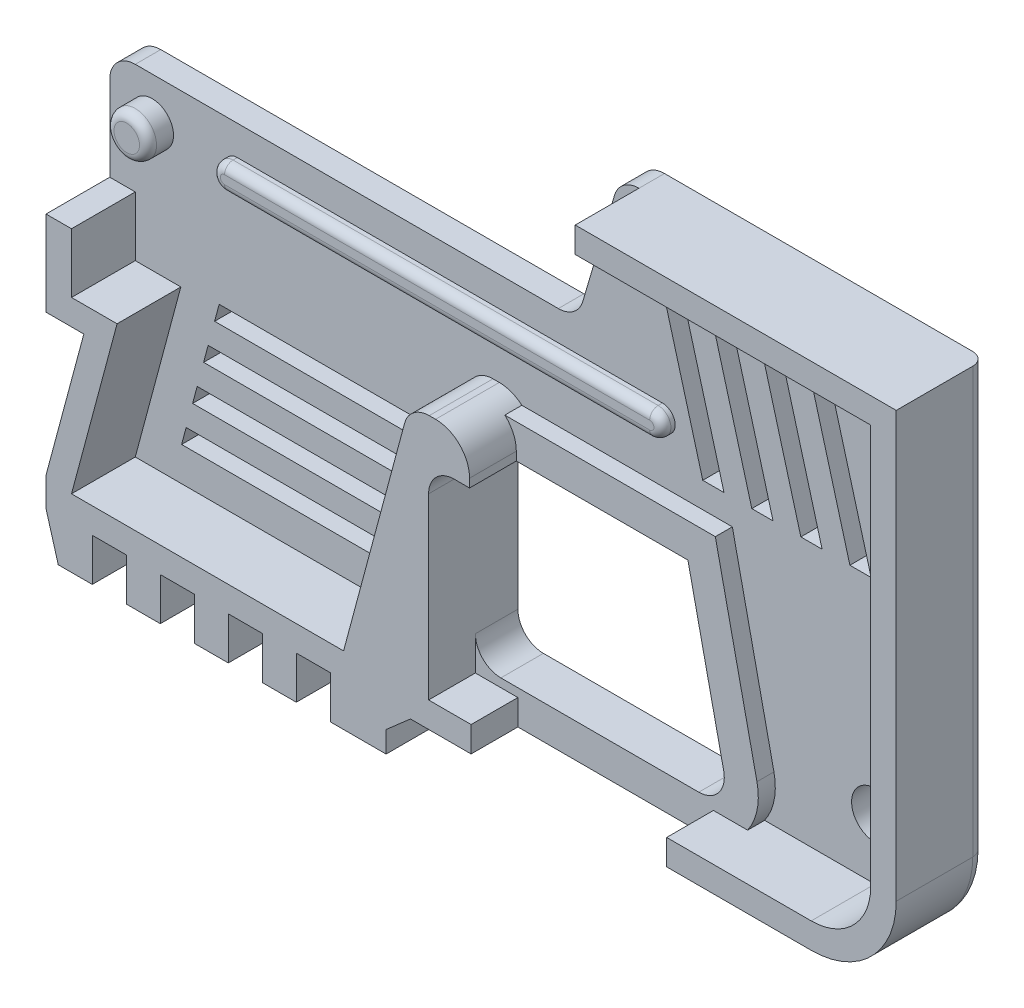
SolidWorks part; units mm, degrees
ref_plane "Front Plane" through (0, 0, 0) normal (0, 0, 1) x (1, 0, 0)
ref_plane "Top Plane" through (0, 0, 0) normal (0, 1, 0) x (1, 0, 0)
ref_plane "Right Plane" through (0, 0, 0) normal (1, 0, 0) x (0, 0, -1)
sketch "Sketch1" plane through (0, 0, 0) normal (0, 0, 1) x (1, 0, 0)
  line L0 (0.6334, 2.1535) -> (4.3666, 14.8465)
  line L1 (7.2447, 17) -> (45, 17)
  line L2 (45, 17) -> (45, -33)
  line L3 (35, -43) -> (-55, -43)
  line L4 (-55, -43) -> (-55, -3)
  line L5 (-52, 0) -> (-2.2447, 0)
  arc A0 (-55, -3) -> (-52, 0) centre (-52, -3) cw
  arc A1 (4.3666, 14.8465) -> (7.2447, 17) centre (7.2447, 14) cw
  arc A2 (0.6334, 2.1535) -> (-2.2447, 0) centre (-2.2447, 3) cw
  arc A3 (45, -33) -> (35, -43) centre (35, -33) cw
  point P9 (-55, 0)
  point P12 (5, 17)
  point P15 (0, 0)
  point P18 (45, -43)
  dimension "D6" = 3
  dimension "D7" = 3
  dimension "D8" = 10
  dimension "D1" = 100
  dimension "D2" = 60
  dimension "D3" = 17
  dimension "D4" = 40
  dimension "D5" = 55
extrude "Boss-Extrude1" add sketch "Sketch1" along normal blind 3
sketch "Sketch2" plane through (0, 0, 3) normal (0, 0, 1) x (1, 0, 0)
  line L0 (-7, -16) -> (15, -16)
  line L1 (15, -16) -> (19.2093, -35.3627)
  line L2 (16.2778, -39) -> (-7, -39)
  line L3 (-10, -36) -> (-10, -19)
  line L4 (-55, -43) -> (35, -43) construction
  line L5 (45, -33) -> (45, 17) construction
  arc A0 (19.2093, -35.3627) -> (16.2778, -39) centre (16.2778, -36) cw
  arc A1 (-7, -39) -> (-10, -36) centre (-7, -36) cw
  arc A2 (-7, -16) -> (-10, -19) centre (-7, -19) ccw
  point P11 (20, -39)
  point P14 (-10, -39)
  point P17 (-10, -16)
  dimension "D6" = 3
  dimension "D1" = 4
  dimension "D2" = 23
  dimension "D3" = 30
  dimension "D4" = 25
  dimension "D5" = 25
extrude "Cut-Extrude1" cut sketch "Sketch2" against normal through all
sketch "Sketch3" plane through (0, 0, 3) normal (0, 0, 1) x (1, 0, 0)
  line L0 (45, -33) -> (45, 17) construction
  line L1 (45, 17) -> (7.2447, 17) construction
  line L2 (45, -33) -> (45, 17)
  line L3 (45, 17) -> (7.2447, 17)
  line L4 (35, -43) -> (18, -43)
  line L5 (-55, -43) -> (35, -43) construction
  line L6 (35, -40) -> (18, -40)
  line L7 (42, -33) -> (42, 14)
  line L8 (42, 14) -> (7.2447, 14)
  line L9 (7.2447, 14) -> (7.2447, 17)
  line L10 (18, -40) -> (18, -43)
  line L11 (-5, -43) -> (-55, -43)
  line L12 (-55, -43) -> (-55, -13)
  line L13 (-55, -3) -> (-55, -43) construction
  line L14 (-55, -13) -> (-52, -13)
  line L15 (-52, -13) -> (-52, -40)
  line L16 (-52, -40) -> (-5, -40)
  line L17 (-5, -40) -> (-5, -43)
  arc A0 (35, -43) -> (45, -33) centre (35, -33) ccw construction
  arc A1 (35, -43) -> (45, -33) centre (35, -33) ccw
  arc A2 (35, -40) -> (42, -33) centre (35, -33) ccw
  dimension "D2" = 17
  dimension "D3" = 3
  dimension "D4" = 30
  dimension "D5" = 50
  dimension "D1" = 3
extrude "Boss-Extrude2" add sketch "Sketch3" along normal blind 7.5
sketch "Sketch4" plane through (0, 0, 3) normal (0, 0, 1) x (1, 0, 0)
  line L0 (15, -16) -> (-7, -16) construction
  line L1 (-10, -19) -> (-10, -36) construction
  line L2 (-7, -39) -> (16.2778, -39) construction
  line L3 (19.2093, -35.3627) -> (15, -16) construction
  line L4 (15, -16) -> (-7, -16)
  line L5 (-10, -19) -> (-10, -36)
  line L6 (-7, -39) -> (16.2778, -39)
  line L7 (19.2093, -35.3627) -> (15, -16)
  line L8 (18.2239, -12) -> (-7, -12)
  line L9 (-14, -19) -> (-14, -36)
  line L10 (-7, -43) -> (16.2778, -43)
  line L11 (23.118, -34.513) -> (18.2239, -12)
  arc A0 (-7, -16) -> (-10, -19) centre (-7, -19) ccw construction
  arc A1 (-10, -36) -> (-7, -39) centre (-7, -36) ccw construction
  arc A2 (16.2778, -39) -> (19.2093, -35.3627) centre (16.2778, -36) ccw construction
  arc A3 (-7, -16) -> (-10, -19) centre (-7, -19) ccw
  arc A4 (-10, -36) -> (-7, -39) centre (-7, -36) ccw
  arc A5 (16.2778, -39) -> (19.2093, -35.3627) centre (16.2778, -36) ccw
  arc A6 (-7, -12) -> (-14, -19) centre (-7, -19) ccw
  arc A7 (-14, -36) -> (-7, -43) centre (-7, -36) ccw
  arc A8 (16.2778, -43) -> (23.118, -34.513) centre (16.2778, -36) ccw
  dimension "D1" = 4
extrude "Boss-Extrude3" add sketch "Sketch4" along normal blind 2
sketch "Sketch5" plane through (0, 0, 3) normal (0, 0, 1) x (1, 0, 0)
  line L0 (9.2447, 11) -> (14.7447, -9)
  line L1 (14.7447, -9) -> (17.2447, -9)
  line L2 (17.2447, -9) -> (11.7447, 11)
  line L3 (11.7447, 11) -> (9.2447, 11)
  line L4 (7.2447, 14) -> (42, 14) construction
  line L5 (23.0125, -9) -> (17.5125, 11)
  line L6 (17.5125, 11) -> (15.0125, 11)
  line L7 (15.0125, 11) -> (20.5125, -9)
  line L8 (20.5125, -9) -> (23.0125, -9)
  line L9 (28.7802, -9) -> (23.2802, 11)
  line L10 (23.2802, 11) -> (20.7802, 11)
  line L11 (20.7802, 11) -> (26.2802, -9)
  line L12 (26.2802, -9) -> (28.7802, -9)
  line L13 (34.548, -9) -> (29.048, 11)
  line L14 (29.048, 11) -> (26.548, 11)
  line L15 (26.548, 11) -> (32.048, -9)
  line L16 (32.048, -9) -> (34.548, -9)
  dimension "D1" = 20
  dimension "D2" = 8
  dimension "D3" = 2.5
  dimension "D4" = 3
  dimension "D5" = 2
  dimension "D6" = 4
extrude "Cut-Extrude2" cut sketch "Sketch5" against normal through all
sketch "Sketch6" plane through (0, 0, 3) normal (0, 0, 1) x (1, 0, 0)
  line L0 (-52, -40) -> (-46.641, -20)
  line L1 (-46.641, -20) -> (-52, -20)
  line L2 (-52, -40) -> (-52, -13) construction
  line L3 (-52, -20) -> (-52, -40)
  dimension "D1" = 15
  dimension "D2" = 20
extrude "Boss-Extrude4" add sketch "Sketch6" along normal blind 7.5
sketch "Sketch7" plane through (0, 0, 10.5) normal (0, 0, 1) x (1, 0, 0)
  line L2 (-55, -13) -> (-55, -43) construction
  line L3 (-55, -39.605) -> (-55, -23)
  line L4 (-54.8978, -39.2235) -> (-50.5507, -23)
  line L5 (-50.5507, -23) -> (-52, -23)
  line L6 (-55, -39.605) -> (-50.5507, -23)
  line L7 (-50.5507, -23) -> (-55, -23)
  dimension "D1" = 3
extrude "Cut-Extrude3" cut sketch "Sketch7" against normal through all
sketch "Sketch8" plane through (0, 0, 3) normal (0, 0, 1) x (1, 0, 0)
  line L0 (-10, -40) -> (-10, -19)
  line L1 (-5, -40) -> (-52, -40) construction
  line L2 (-7, -16) -> (-5.1831, -16)
  line L3 (-5.1831, -16) -> (-5.1831, -11)
  line L4 (-5.1831, -11) -> (-9.9275, -11)
  line L5 (-12.8253, -13.2235) -> (-20, -40)
  line L6 (-52, -40) -> (-46.641, -20) construction
  line L7 (15, -16) -> (-7, -16) construction
  line L8 (-20, -40) -> (-10, -40)
  arc A0 (-10, -19) -> (-7, -16) centre (-7, -19) cw
  arc A1 (-9.9275, -11) -> (-12.8253, -13.2235) centre (-9.9275, -14) ccw
  dimension "D1" = 3
  dimension "D2" = 3
  dimension "D3" = 5
  dimension "D4" = 10
extrude "Boss-Extrude5" add sketch "Sketch8" along normal blind 7.5
sketch "Sketch9" plane through (0, 0, 3) normal (0, 0, 1) x (1, 0, 0)
  line L0 (-40, -5) -> (10, -5) construction
  line L1 (-40, -3.5) -> (10, -3.5)
  line L2 (-40, -6.5) -> (10, -6.5)
  line L3 (-2.2447, 0) -> (-52, 0) construction
  line L4 (-55, -3) -> (-55, -13) construction
  arc A0 (-40, -3.5) -> (-40, -6.5) centre (-40, -5) ccw
  arc A1 (10, -6.5) -> (10, -3.5) centre (10, -5) ccw
  point P2 (-15, -5)
  point P9 (-27.1224, 0)
  dimension "D1" = 3
  dimension "D2" = 50
  dimension "D3" = 5
  dimension "D4" = 15
sketch "Sketch10" plane through (0, 0, 3) normal (0, 0, 1) x (1, 0, 0)
  line L0 (-2.2447, 0) -> (-52, 0) construction
  line L1 (-55, -3) -> (-55, -13) construction
  circle A0 centre (-50, -5) radius 2.5
  dimension "D3" = 5
  dimension "D1" = 5
  dimension "D2" = 5
extrude "Boss-Extrude6" add sketch "Sketch10" along normal blind 3
fillet "Fillet2" radius 1 1 edges at (-47.5, -5, 6)
sketch "Sketch11" plane through (0, 0, 3) normal (0, 0, 1) x (1, 0, 0)
  circle A0 centre (35, -33) radius 2.75
  dimension "D1" = 5.5
extrude "Cut-Extrude5" cut sketch "Sketch11" against normal through all
fillet "Fillet3" radius 1.5 3 edges at (-10, -43, 0) (42.0711, -40.0711, 0) (45, -8, 0)
sketch "Sketch12" plane through (0, 0, 3) normal (0, 0, 1) x (1, 0, 0)
  line L0 (-46.5517, -36) -> (-22.5517, -36)
  line L1 (-22.5517, -36) -> (-22.0158, -34)
  line L2 (-22.0158, -34) -> (-46.0158, -34)
  line L3 (-46.0158, -34) -> (-46.5517, -36)
  line L4 (-52, -40) -> (-46.641, -20) construction
  line L5 (-12.8253, -13.2235) -> (-20, -40) construction
  line L6 (-20, -40) -> (-52, -40) construction
  line L7 (-45.2576, -31.1704) -> (-21.2576, -31.1704)
  line L8 (-21.2576, -31.1704) -> (-20.7217, -29.1704)
  line L9 (-20.7217, -29.1704) -> (-44.7217, -29.1704)
  line L10 (-44.7217, -29.1704) -> (-45.2576, -31.1704)
  line L11 (-43.9635, -26.3407) -> (-19.9635, -26.3407)
  line L12 (-19.9635, -26.3407) -> (-19.4276, -24.3407)
  line L13 (-19.4276, -24.3407) -> (-43.4276, -24.3407)
  line L14 (-43.4276, -24.3407) -> (-43.9635, -26.3407)
  line L15 (-42.6694, -21.5111) -> (-18.6694, -21.5111)
  line L16 (-18.6694, -21.5111) -> (-18.1335, -19.5111)
  line L17 (-18.1335, -19.5111) -> (-42.1335, -19.5111)
  line L18 (-42.1335, -19.5111) -> (-42.6694, -21.5111)
  dimension "D1" = 2
  dimension "D2" = 24
  dimension "D3" = 3.5
  dimension "D4" = 4
  dimension "D5" = 4
extrude "Cut-Extrude6" cut sketch "Sketch12" against normal through all
sketch "Sketch13" plane through (0, 0, 0) normal (0, 0, 1) x (1, 0, 0)
  line L0 (-55, -43) -> (-53.5586, -48.0092)
  line L1 (-53.5586, -48.0092) -> (-14.9974, -48.0092)
  line L2 (-14.9974, -48.0092) -> (-14.9974, -45.5046)
  line L3 (-14.9974, -45.5046) -> (-12.1335, -43)
  line L4 (-55, -43) -> (-5, -43) construction
  line L5 (-12.1335, -43) -> (-55, -43)
extrude "Boss-Extrude7" add sketch "Sketch13" along normal blind 10.5
chamfer "Chamfer1" distance 1 angle 45 2 edges at (-33.5667, -43, 0) (-34.278, -48.0092, 0)
sketch "Sketch14" plane through (0, 0, 10.5) normal (0, 0, 1) x (1, 0, 0)
  line L0 (-53.5586, -48.0092) -> (-14.9974, -48.0092) construction
  line L1 (-49.5586, -48.0092) -> (-45.5586, -48.0092)
  line L2 (-49.5586, -48.0092) -> (-49.5586, -43)
  line L3 (-49.5586, -43) -> (-45.5586, -43)
  line L4 (-45.5586, -48.0092) -> (-45.5586, -43)
  line L5 (-20, -40) -> (-52, -40) construction
  line L6 (-41.5586, -43) -> (-37.5586, -43)
  line L7 (-37.5586, -48.0092) -> (-37.5586, -43)
  line L8 (-41.5586, -48.0092) -> (-37.5586, -48.0092)
  line L9 (-41.5586, -48.0092) -> (-41.5586, -43)
  line L10 (-33.5586, -43) -> (-29.5586, -43)
  line L11 (-29.5586, -48.0092) -> (-29.5586, -43)
  line L12 (-33.5586, -48.0092) -> (-29.5586, -48.0092)
  line L13 (-33.5586, -48.0092) -> (-33.5586, -43)
  line L14 (-25.5586, -43) -> (-21.5586, -43)
  line L15 (-21.5586, -48.0092) -> (-21.5586, -43)
  line L16 (-25.5586, -48.0092) -> (-21.5586, -48.0092)
  line L17 (-25.5586, -48.0092) -> (-25.5586, -43)
  dimension "D1" = 4
  dimension "D2" = 4
  dimension "D3" = 3
  dimension "D4" = 4
extrude "Cut-Extrude7" cut sketch "Sketch14" against normal through all
extrude "Boss-Extrude8" add sketch "Sketch9" along normal blind 1.5
fillet "Fillet4" radius 1 4 edges at (-15, -3.5, 4.5) (11.5, -5, 4.5) (-15, -6.5, 4.5) (-41.5, -5, 4.5)
fillet "Fillet5" radius 4 1 edges at (-5.1831, -11, 6.75)
